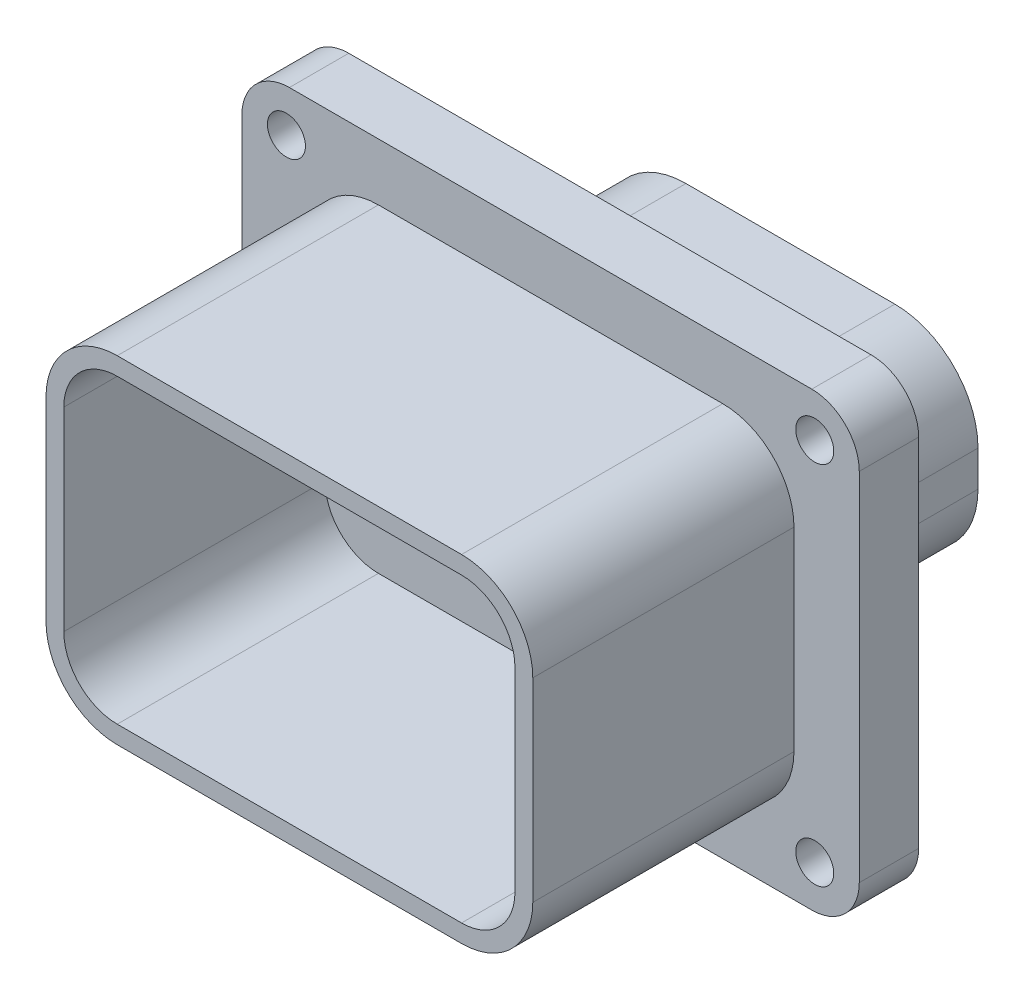
SolidWorks part; units mm, degrees
ref_plane "Front Plane" through (0, 0, 0) normal (0, 0, 1) x (1, 0, 0)
ref_plane "Top Plane" through (0, 0, 0) normal (0, 1, 0) x (1, 0, 0)
ref_plane "Right Plane" through (0, 0, 0) normal (1, 0, 0) x (0, 0, -1)
sketch "Sketch2" plane through (0, 0, 0) normal (0, 0, 1) x (1, 0, 0)
  line L0 (405.5272, 271.0599) -> (972.1938, 271.0599) construction
sketch "Sketch1" plane through (0, 0, 0) normal (0, 0, 1) x (1, 0, 0)
  line L1 (0, 0) -> (52, 0)
  line L2 (0, 0) -> (0, 38)
  line L3 (0, 38) -> (52, 38)
  line L4 (52, 0) -> (52, 38)
  line L5 (3.75, 3.6) -> (48.25, 3.6)
  line L6 (3.75, 3.6) -> (3.75, 34.4)
  line L7 (3.75, 34.4) -> (48.25, 34.4)
  line L8 (48.25, 3.6) -> (48.25, 34.4)
  line L9 (3.75, 3.6) -> (48.25, 34.4) construction
  line L10 (3.75, 34.4) -> (48.25, 3.6) construction
  circle A0 centre (3.75, 34.4) radius 1.6
  circle A1 centre (48.25, 34.4) radius 1.6
  circle A2 centre (48.25, 3.6) radius 1.6
  circle A3 centre (3.75, 3.6) radius 1.6
  point P5 (26, 19)
  point P11 (26, 38)
  point P13 (52, 19)
  dimension "D5" = 3.2
  dimension "D1" = 52
  dimension "D2" = 38
  dimension "D3" = 44.5
  dimension "D4" = 30.8
extrude "Boss-Extrude1" add sketch "Sketch1" along normal blind 5 contours L1 L4 L3 L2 A3 L6 A0 L7 A1 L8 A2 L5 | A3 L5 A2 L8 A1 L7 A0 L6
sketch "Sketch3" plane through (0, 0, 0) normal (1, 0, 0) x (0, 0, -1)
  line L0 (-44.7548, 277.6479) -> (-104.7521, 134.4861) construction
sketch "Sketch5" plane through (0, 0, 0) normal (0, 0, -1) x (-1, 0, 0)
  line L0 (-52, 38) -> (0, 0) construction
  line L1 (-41.8, 27.5) -> (-10.2, 27.5)
  line L2 (-41.8, 27.5) -> (-41.8, 10.5)
  line L3 (-41.8, 10.5) -> (-10.2, 10.5)
  line L4 (-10.2, 27.5) -> (-10.2, 10.5)
  point P8 (-26, 19)
  point P9 (-26, 27.5)
  point P10 (-10.2, 19)
  dimension "D1" = 31.6
  dimension "D2" = 17
extrude "Boss-Extrude2" add sketch "Sketch5" along normal blind 15.2
sketch "Sketch7" plane through (0, 0, 5) normal (0, 0, 1) x (1, 0, 0)
  line L0 (3.75, 34.4) -> (48.25, 3.6) construction
  line L1 (11.5, 33.1888) -> (40.5, 33.1888)
  line L2 (5.5, 27.1888) -> (5.5, 10.8112)
  line L3 (11.5, 4.8112) -> (40.5, 4.8112)
  line L4 (46.5, 27.1888) -> (46.5, 10.8112)
  line L5 (11.5, 31.6888) -> (40.5, 31.6888)
  line L6 (45, 27.1888) -> (45, 10.8112)
  line L7 (11.5, 6.3112) -> (40.5, 6.3112)
  line L8 (7, 27.1888) -> (7, 10.8112)
  arc A0 (5.5, 10.8112) -> (11.5, 4.8112) centre (11.5, 10.8112) ccw
  arc A1 (40.5, 4.8112) -> (46.5, 10.8112) centre (40.5, 10.8112) ccw
  arc A2 (40.5, 33.1888) -> (46.5, 27.1888) centre (40.5, 27.1888) cw
  arc A3 (11.5, 33.1888) -> (5.5, 27.1888) centre (11.5, 27.1888) ccw
  arc A4 (40.5, 31.6888) -> (45, 27.1888) centre (40.5, 27.1888) cw
  arc A5 (40.5, 6.3112) -> (45, 10.8112) centre (40.5, 10.8112) ccw
  arc A6 (7, 10.8112) -> (11.5, 6.3112) centre (11.5, 10.8112) ccw
  arc A7 (11.5, 31.6888) -> (7, 27.1888) centre (11.5, 27.1888) ccw
  point P8 (26, 33.1888)
  point P9 (26, 19)
  point P10 (46.5, 19)
  point P11 (46.5, 4.0192)
  point P12 (48.25, 3.6)
  point P14 (3.75, 34.4)
  point P20 (46.5, 4.8112)
  point P23 (46.5, 33.1888)
  point P26 (5.5, 33.1888)
  dimension "D2" = 6
  dimension "D1" = 41
  dimension "D3" = 1.5
extrude "Boss-Extrude3" add sketch "Sketch7" along normal offset from surface (22 mm away) 27 up to face at (26, 19, 0)
fillet "Fillet1" radius 4 4 edges at (0, 0, 2.5) (0, 38, 2.5) (52, 0, 2.5) (52, 38, 2.5)
fillet "Fillet2" radius 7 4 edges at (41.8, 10.5, -7.6) (41.8, 27.5, -7.6) (10.2, 10.5, -7.6) (10.2, 27.5, -7.6)
